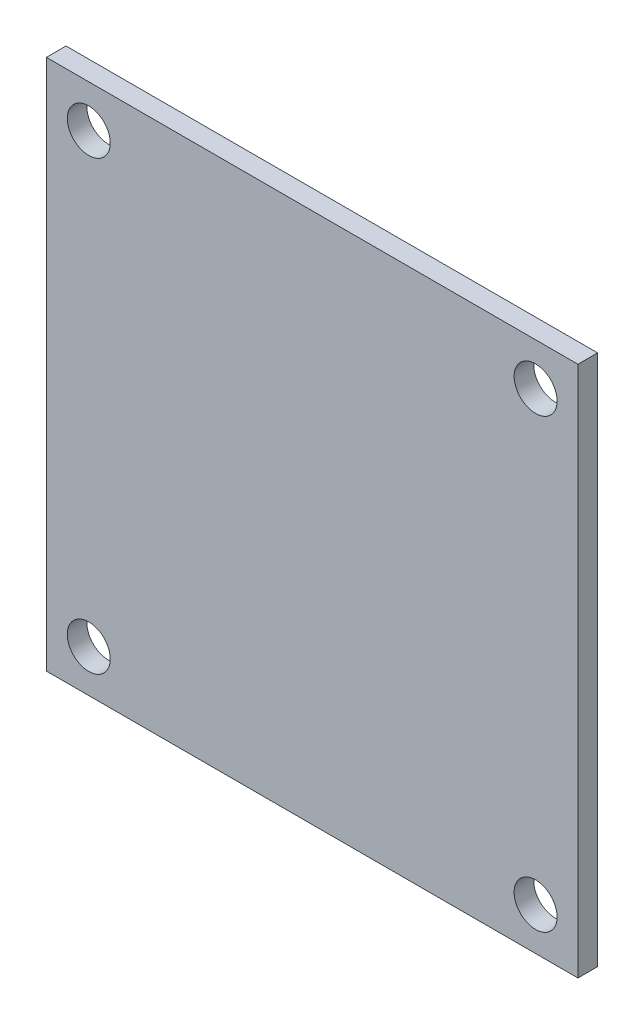
SolidWorks part; units mm, degrees
ref_plane "Plan de face" through (0, 0, 0) normal (0, 0, 1) x (1, 0, 0)
ref_plane "Plan de dessus" through (0, 0, 0) normal (0, 1, 0) x (1, 0, 0)
ref_plane "Plan de droite" through (0, 0, 0) normal (1, 0, 0) x (0, 0, -1)
sketch "Esquisse1" plane through (0, 0, 0) normal (0, 0, 1) x (1, 0, 0)
  line L1 (0, 0) -> (43.3, 0)
  line L2 (0, 0) -> (0, 43.3)
  line L3 (0, 43.3) -> (43.3, 43.3)
  line L4 (43.3, 0) -> (43.3, 43.3)
  dimension "D1" = 43.3
  dimension "D2" = 43.3
extrude "Boss.-Extru.1" add sketch "Esquisse1" along normal blind 1.6
sketch "Esquisse2" plane through (0, 0, 1.6) normal (0, 0, 1) x (1, 0, 0)
  line L0 (43.3, 43.3) -> (0, 43.3) construction
  line L1 (0, 43.3) -> (0, 0) construction
  circle A0 centre (3.45, 39.85) radius 1.75
  point P4 (21.65, 43.3)
  point P7 (0, 21.65)
  dimension "D1" = 3.5
  dimension "D2" = 18.2
  dimension "D3" = 18.2
extrude "Enlèv. mat.-Extru.1" cut sketch "Esquisse2" against normal through all
ref_plane "Plan1" through (21.65, 0, 0) normal (-1, 0, 0) x (0, 0, 1)
ref_plane "Plan2" through (0, 21.65, 0) normal (0, 1, 0) x (1, 0, 0)
mirror "Symétrie1" about plane through (21.65, 0, 0) normal (-1, 0, 0) of "Enlèv. mat.-Extru.1"
mirror "Symétrie2" about plane through (0, 21.65, 0) normal (0, 1, 0) of "Symétrie1", "Enlèv. mat.-Extru.1"
